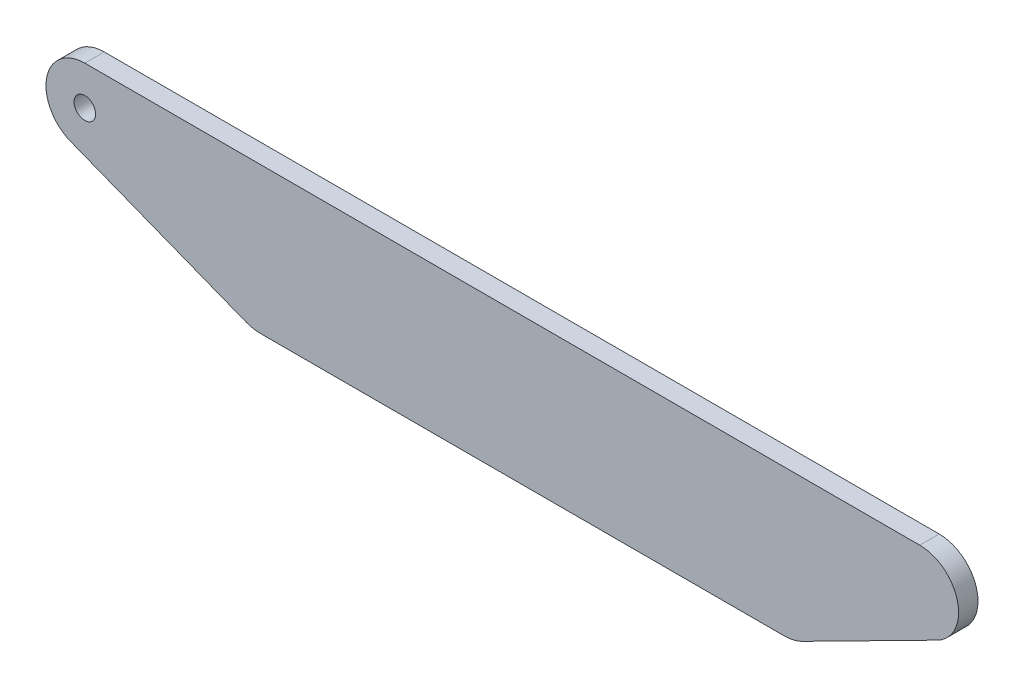
SolidWorks part; units mm, degrees
material "POLYURETHANE (11671)"
ref_plane "Front Plane" through (0, 0, 0) normal (0, 0, 1) x (1, 0, 0)
ref_plane "Top Plane" through (0, 0, 0) normal (0, 1, 0) x (1, 0, 0)
ref_plane "Right Plane" through (0, 0, 0) normal (1, 0, 0) x (0, 0, -1)
sketch "Sketch1" plane through (0, 0, 0) normal (0, 0, 1) x (1, 0, 0)
  line L0 (-44.8305, -428.0489) -> (495.1695, -428.0489)
  line L1 (-225.5412, -277.3382) -> (634.4588, -277.3382)
  line L8 (513.2761, -423.7161) -> (652.5654, -353.0055)
  line L13 (-240.1168, -354.5881) -> (-59.4061, -425.2988)
  line L28 (-44.8305, -388.0489) -> (-115.5412, -317.3382) construction
  line L34 (135.1695, -388.0489) -> (64.4588, -317.3382) construction
  line L39 (315.1695, -388.0489) -> (244.4588, -317.3382) construction
  line L40 (495.1695, -388.0489) -> (424.4588, -317.3382) construction
  line L46 (-245.5412, -257.3382) -> (644.4588, -257.3382) construction
  line L47 (-115.5412, -372.3382) -> (584.4588, -372.3382) construction
  line L48 (644.4588, -337.3382) -> (584.4588, -372.3382) construction
  line L49 (-115.5412, -372.3382) -> (-245.5412, -337.3382) construction
  line L50 (-245.5412, -337.3382) -> (-245.5412, -257.3382) construction
  line L51 (644.4588, -257.3382) -> (644.4588, -337.3382) construction
  circle A45 centre (-115.5412, -317.3382) radius 11.9875 construction
  circle A52 centre (-44.8305, -388.0489) radius 40 construction
  circle A53 centre (64.4588, -317.3382) radius 11.9875 construction
  circle A58 centre (244.4588, -317.3382) radius 11.9875 construction
  circle A63 centre (424.4588, -317.3382) radius 11.9875 construction
  circle A69 centre (135.1695, -388.0489) radius 40 construction
  circle A70 centre (315.1695, -388.0489) radius 40 construction
  circle A71 centre (495.1695, -388.0489) radius 40 construction
  circle A73 centre (634.4588, -317.3382) radius 40 construction
  circle A78 centre (-225.5412, -317.3382) radius 11.1125
  circle A79 centre (-225.5412, -317.3382) radius 40 construction
  arc A90 (-225.5412, -277.3382) -> (-240.1168, -354.5881) centre (-225.5412, -317.3382) ccw
  arc A91 (-44.8305, -428.0489) -> (-59.4061, -425.2988) centre (-44.8305, -388.0489) cw
  arc A92 (513.2761, -423.7161) -> (495.1695, -428.0489) centre (495.1695, -388.0489) cw
  arc A93 (634.4588, -277.3382) -> (652.5654, -353.0055) centre (634.4588, -317.3382) cw
  dimension "D1" = 860
extrude "Boss-Extrude1" add sketch "Sketch1" along normal blind 20 contours L1 A93 L8 A92 L0 A91 L13 A90
